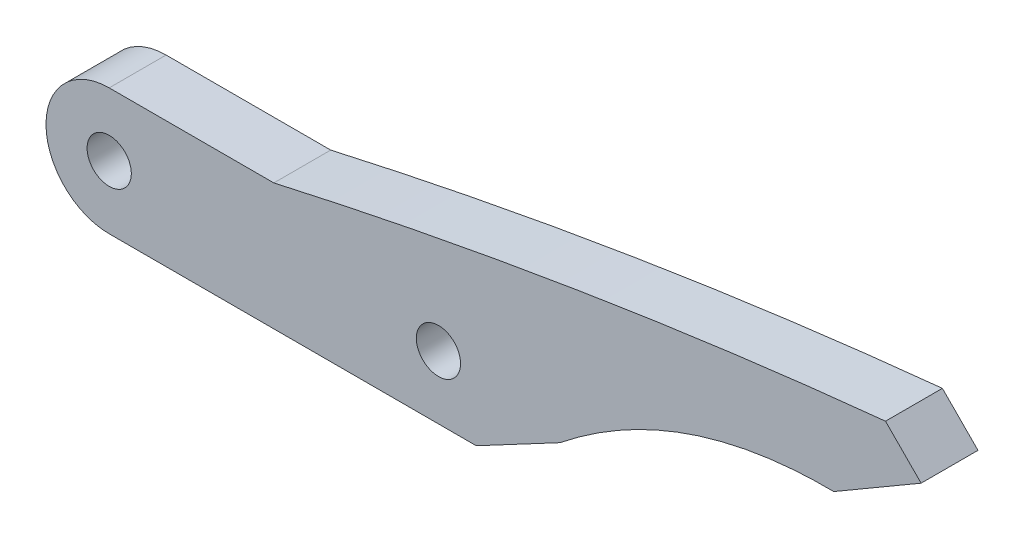
SolidWorks part; units mm, degrees
ref_plane "Front Plane" through (0, 0, 0) normal (0, 0, 1) x (1, 0, 0)
ref_plane "Top Plane" through (0, 0, 0) normal (0, 1, 0) x (1, 0, 0)
ref_plane "Right Plane" through (0, 0, 0) normal (1, 0, 0) x (0, 0, -1)
sketch "Sketch1" plane through (0, 0, 0) normal (0, 0, 1) x (1, 0, 0)
  line L0 (-13.0231, 0) -> (8.9769, 0) construction
  line L1 (0, 5.8667) -> (0, -5.9714) construction
  line L3 (18.0231, -5) -> (-18.0231, -5)
  line L4 (18.0231, -5) -> (18.0231, 5)
  line L5 (18.0231, 5) -> (-18.0231, 5)
  line L6 (-18.0231, -5) -> (-18.0231, 5)
  line L7 (18.0231, -5) -> (-18.0231, 5) construction
  line L8 (18.0231, 5) -> (-18.0231, -5) construction
  circle A0 centre (-13.0231, 0) radius 1.75
  circle A1 centre (-13.0231, 0) radius 5
  circle A2 centre (13.0231, 0) radius 5
  circle A3 centre (13.0231, 0) radius 1.75
  point P10 (0, 0)
  dimension "D2" = 3.5
  dimension "D3" = 10
  dimension "D1" = 22
extrude "Boss-Extrude1" add sketch "Sketch1" along normal blind 4.5 contours A1 A0 | A2 A3 | L3 A2 L5 A1
sketch "Sketch2" plane through (0, 0, 4.5) normal (0, 0, 1) x (1, 0, 0)
  line L0 (48.3871, 12.87) -> (51.2039, 10.03)
  line L1 (51.2039, 10.03) -> (44.2931, 6)
  line L2 (13.0231, -5) -> (-13.0231, -5) construction
  line L3 (13.0231, 0) -> (13.0231, -5) construction
  line L4 (22.6331, -1.48) -> (16.0131, -5)
  line L5 (16.0131, -5) -> (13.0231, -5)
  line L6 (13.0231, 5) -> (-13.0231, 5) construction
  line L7 (13.0231, 5) -> (0, 5)
  arc A0 (13.0231, -5) -> (13.0231, 5) centre (13.0231, 0) ccw construction
  arc A1 (13.0231, -5) -> (13.0231, 5) centre (13.0231, 0) ccw
  spline S0 degree 2 poles (44.2931, 6) (32.1692, 6.1573) (22.6331, -1.48) knots 0 0 0 1 1 1
  spline S1 degree 2 poles (0, 5) (23.9571, 10.4181) (48.3871, 12.87) knots 0 0 0 1 1 1
  dimension "D3" = 17.87
  dimension "D1" = 4
  dimension "D2" = 8
  dimension "D4" = 15.03
  dimension "D5" = 11
  dimension "D6" = 9.45
  dimension "D7" = 3.52
  dimension "D8" = 9.61
  dimension "D9" = 20.52
  dimension "D10" = 31.27
  dimension "D11" = 2.99
  dimension "D12" = 28.001
  dimension "D13" = 13.52
  dimension "D14" = 15.07
extrude "Boss-Extrude2" add sketch "Sketch2" against normal up to surface (4.5 mm away) up to face at (-11.2731, 0, 0)
